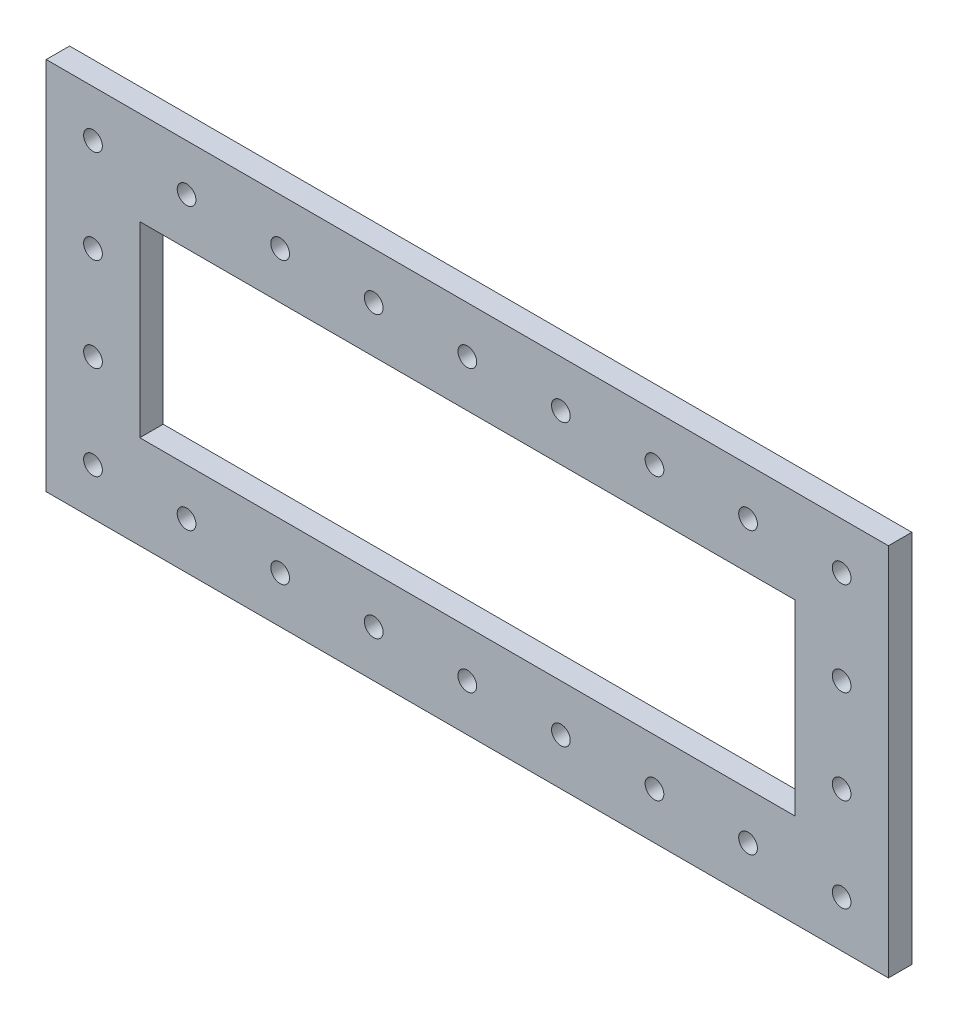
SolidWorks part; units mm, degrees
ref_plane "Front Plane" through (0, 0, 0) normal (0, 0, 1) x (1, 0, 0)
ref_plane "Top Plane" through (0, 0, 0) normal (0, 1, 0) x (1, 0, 0)
ref_plane "Right Plane" through (0, 0, 0) normal (1, 0, 0) x (0, 0, -1)
sketch "Sketch1" plane through (0, 0, 0) normal (0, 0, 1) x (1, 0, 0)
  line L0 (0, 0) -> (0, 50.8)
  line L1 (0, 50.8) -> (25.4, 50.8)
  line L2 (25.4, 50.8) -> (25.4, 25.4)
  line L5 (228.6, 0) -> (0, 0)
  line L6 (25.4, 25.4) -> (203.2, 25.4)
  line L7 (203.2, 25.4) -> (203.2, 50.8)
  line L8 (203.2, 50.8) -> (228.6, 50.8)
  line L9 (228.6, 50.8) -> (228.6, 0)
  dimension "D1" = 50.8
  dimension "D2" = 25.4
  dimension "D3" = 25.4
  dimension "3" = 228.6
extrude "Boss-Extrude1" add sketch "Sketch1" along normal blind 6.35
sketch "Sketch2" plane through (0, 0, 6.35) normal (0, 0, 1) x (1, 0, 0)
  line L0 (25.4, 50.8) -> (0, 50.8) construction
  line L1 (25.4, 25.4) -> (25.4, 50.8) construction
  line L2 (0, 0) -> (228.6, 0) construction
  line L3 (114.3, 25.4) -> (114.3, 0) construction
  line L6 (203.2, 25.4) -> (25.4, 25.4) construction
  line L7 (0, 0) -> (228.6, 0) construction
  circle A0 centre (12.7, 38.1) radius 2.54
  circle A1 centre (12.7, 12.7) radius 2.54
  circle A11 centre (38.1, 12.7) radius 2.54
  circle A12 centre (63.5, 12.7) radius 2.54
  circle A13 centre (88.9, 12.7) radius 2.54
  circle A14 centre (114.3, 12.7) radius 2.54
  circle A15 centre (139.7, 12.7) radius 2.54
  circle A16 centre (165.1, 12.7) radius 2.54
  circle A17 centre (190.5, 12.7) radius 2.54
  circle A18 centre (215.9, 12.7) radius 2.54
  circle A19 centre (215.9, 38.1) radius 2.54
  dimension "D1" = 5.08
  dimension "D2" = 12.7
  dimension "D3" = 12.7
  dimension "D4" = 12.7
  dimension "D5" = 9
extrude "Cut-Extrude1" cut sketch "Sketch2" against normal through all
mirror "Mirror2" about plane through (0, 50.8, 6.35) normal (0, -1, 0) of "Cut-Extrude1", "Boss-Extrude1"
